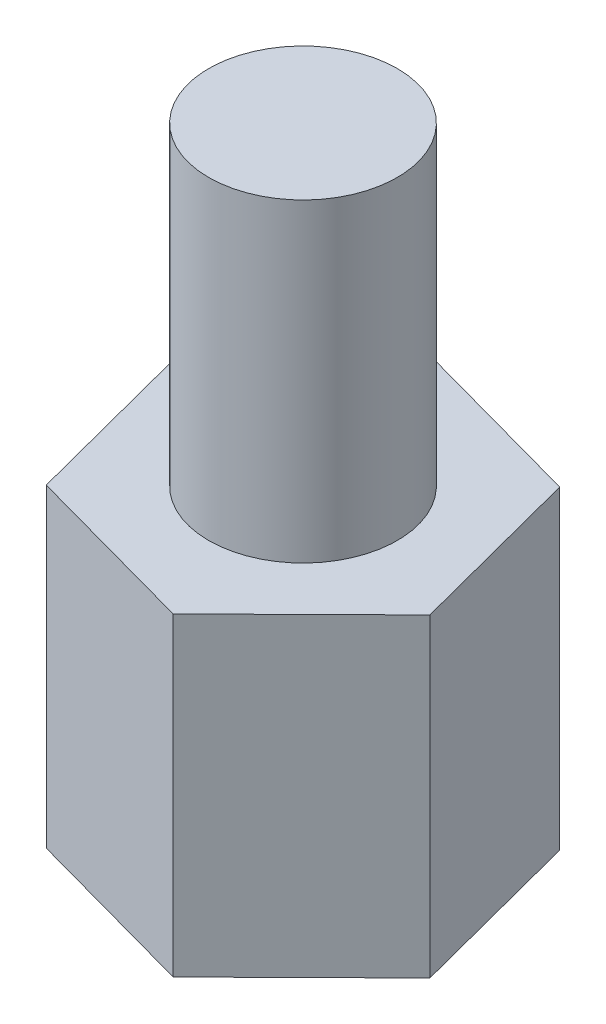
SolidWorks part; units mm, degrees
material "橡胶"
ref_plane "前视基准面" through (0, 0, 0) normal (0, 0, 1) x (1, 0, 0)
ref_plane "上视基准面" through (0, 0, 0) normal (0, 1, 0) x (1, 0, 0)
ref_plane "右视基准面" through (0, 0, 0) normal (1, 0, 0) x (0, 0, -1)
sketch "草图1" plane through (0, 0, 0) normal (0, 1, 0) x (1, 0, 0)
  line L1 (0.7287, -2.7933) -> (2.7834, -0.7656)
  line L2 (2.7834, -0.7656) -> (2.0547, 2.0277)
  line L3 (2.0547, 2.0277) -> (-0.7287, 2.7933)
  line L4 (-0.7287, 2.7933) -> (-2.7834, 0.7656)
  line L5 (-2.7834, 0.7656) -> (-2.0547, -2.0277)
  line L6 (-2.0547, -2.0277) -> (0.7287, -2.7933)
  circle A0 centre (0, 0) radius 2.5 construction
extrude "凸台-拉伸1" add sketch "草图1" along normal blind 5
sketch "草图2" plane through (0, 5, 0) normal (0, 1, 0) x (1, 0, 0)
  circle A0 centre (0, 0) radius 1.5
extrude "凸台-拉伸2" add sketch "草图2" along normal blind 5
sketch "草图3" plane through (0, 0, 0) normal (0, -1, 0) x (1, 0, 0)
  circle A0 centre (0, 0) radius 1.5
extrude "切除-拉伸1" cut sketch "草图3" against normal blind 5
